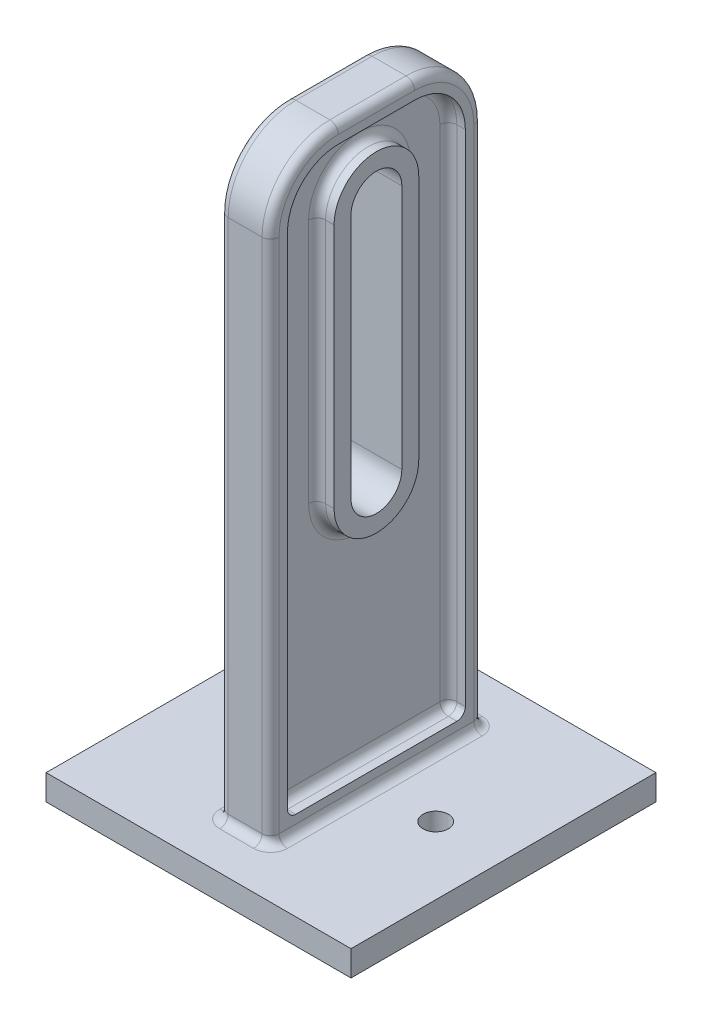
SolidWorks part; units mm, degrees
ref_plane "Front Plane" through (0, 0, 0) normal (0, 0, 1) x (1, 0, 0)
ref_plane "Top Plane" through (0, 0, 0) normal (0, 1, 0) x (1, 0, 0)
ref_plane "Right Plane" through (0, 0, 0) normal (1, 0, 0) x (0, 0, -1)
sketch "Sketch1" plane through (0, 0, 0) normal (0, 1, 0) x (1, 0, 0)
  line L1 (-18, 18) -> (18, 18)
  line L2 (-18, 18) -> (-18, -18)
  line L3 (-18, -18) -> (18, -18)
  line L4 (18, 18) -> (18, -18)
  line L5 (-18, 18) -> (18, -18) construction
  line L6 (-18, -18) -> (18, 18) construction
  point P0 (0, 0)
  dimension "D1" = 36
  dimension "D2" = 36
extrude "Boss-Extrude1" add sketch "Sketch1" along normal blind 3
sketch "Sketch2" plane through (0, 3, 0) normal (0, 1, 0) x (1, 0, 0)
  line L0 (-19.4305, 0) -> (19.8471, 0) construction
  line L1 (0, -25.0629) -> (0, 24.457) construction
  circle A0 centre (-10, 0) radius 1.5
  circle A1 centre (10, 0) radius 1.5
  dimension "D1" = 3
  dimension "D2" = 20
extrude "Cut-Extrude1" cut sketch "Sketch2" against normal through all
sketch "Sketch3" plane through (0, 3, 0) normal (0, 1, 0) x (1, 0, 0)
  line L1 (-3, -12.5) -> (3, -12.5)
  line L2 (-3, -12.5) -> (-3, 12.5)
  line L3 (-3, 12.5) -> (3, 12.5)
  line L4 (3, -12.5) -> (3, 12.5)
  line L5 (-3, -12.5) -> (3, 12.5) construction
  line L6 (-3, 12.5) -> (3, -12.5) construction
  point P0 (0, 0)
  dimension "D1" = 25
  dimension "D2" = 6
extrude "Boss-Extrude2" add sketch "Sketch3" along normal blind 70
sketch "Sketch4" plane through (-3, 0, 0) normal (-1, 0, 0) x (0, 0, 1)
  line L0 (0, -10.7395) -> (0, 80.1502) construction
  line L1 (-28.4656, 0) -> (25.2112, 0) construction
  line L2 (0, 34) -> (0, 63) construction
  line L5 (-3, 34) -> (-3, 63)
  line L6 (3, 34) -> (3, 63)
  line L7 (-12.5, 73) -> (12.5, 73) construction
  arc A2 (-3, 34) -> (3, 34) centre (0, 34) ccw
  arc A3 (3, 63) -> (-3, 63) centre (0, 63) ccw
  point P7 (0, 48.5)
  dimension "D1" = 3
  dimension "D2" = 10
  dimension "D3" = 29
extrude "Cut-Extrude2" cut sketch "Sketch4" against normal through all
fillet "Fillet1" radius 8 2 edges at (0, 73, -12.5) (0, 73, 12.5)
sketch "Sketch5" plane through (-3, 0, 0) normal (-1, 0, 0) x (0, 0, 1)
  line L12 (4.5, 71) -> (-4.5, 71)
  line L13 (-10.5, 65) -> (-10.5, 5)
  line L14 (-10.5, 5) -> (10.5, 5)
  line L15 (10.5, 5) -> (10.5, 65)
  line L16 (4.5, 71) -> (-4.5, 71)
  line L17 (-10.5, 65) -> (-10.5, 5)
  line L18 (-10.5, 5) -> (10.5, 5)
  line L19 (10.5, 5) -> (10.5, 65)
  line L24 (5, 34) -> (5, 63)
  line L25 (-5, 63) -> (-5, 34)
  line L26 (5, 34) -> (5, 63)
  line L27 (-5, 63) -> (-5, 34)
  arc A6 (-4.5, 71) -> (-10.5, 65) centre (-4.5, 65) ccw
  arc A7 (10.5, 65) -> (4.5, 71) centre (4.5, 65) ccw
  arc A8 (-4.5, 71) -> (-10.5, 65) centre (-4.5, 65) ccw
  arc A9 (10.5, 65) -> (4.5, 71) centre (4.5, 65) ccw
  arc A14 (-5, 34) -> (5, 34) centre (0, 34) ccw
  arc A15 (5, 63) -> (-5, 63) centre (0, 63) ccw
  arc A16 (-5, 34) -> (5, 34) centre (0, 34) ccw
  arc A17 (5, 63) -> (-5, 63) centre (0, 63) ccw
  dimension "D1" = 2
  dimension "D2" = 2
extrude "Cut-Extrude3" cut sketch "Sketch5" against normal blind 2
mirror "Mirror1" about plane through (0, 0, 0) normal (1, 0, 0) of "Cut-Extrude3"
fillet "Fillet2" radius 1 14 edges at (-1, 29, 0) (-1, 48.5, -5) (-1, 68, 0) (-3, 34, -12.5) (-3, 70.6569, -10.1569) (-3, 73, 0) (-3, 70.6569, 10.1569) (-1, 35, -10.5) (-1, 69.2426, -8.7426) (-1, 71, 0) (-1, 69.2426, 8.7426) (-1, 48.5, 5) (-3, 34, 12.5) (-1, 35, 10.5)
fillet "Fillet3" radius 1 5 edges at (-2.5, 5, -10.5) (-1.2929, 5, -10.2071) (-2.5, 5, 10.5) (-1.2929, 5, 10.2071) (-1, 5, 0)
fillet "Fillet6" radius 1 14 edges at (3, 34, -12.5) (3, 70.6569, -10.1569) (3, 73, 0) (3, 70.6569, 10.1569) (1, 29, 0) (1, 48.5, -5) (1, 68, 0) (1, 35, 10.5) (1, 69.2426, 8.7426) (1, 71, 0) (1, 69.2426, -8.7426) (3, 34, 12.5) (1, 48.5, 5) (1, 35, -10.5)
fillet "Fillet7" radius 1 5 edges at (2.5, 5, -10.5) (1.2929, 5, -10.2071) (2.5, 5, 10.5) (1.2929, 5, 10.2071) (1, 5, 0)
fillet "Fillet8" radius 1 8 edges at (2.7071, 3, 12.2071) (0, 3, 12.5) (-2.7071, 3, 12.2071) (-3, 3, 0) (-2.7071, 3, -12.2071) (0, 3, -12.5) (2.7071, 3, -12.2071) (3, 3, 0)
